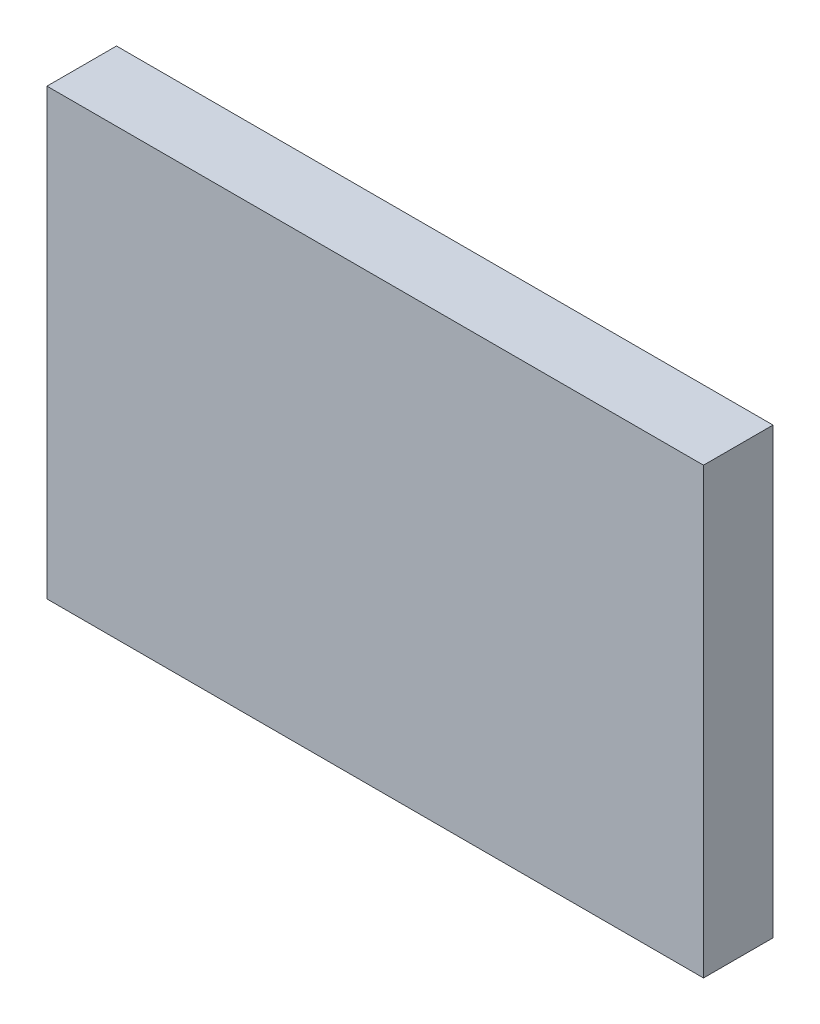
SolidWorks part; units mm, degrees
ref_plane "Alzado" through (0, 0, 0) normal (0, 0, 1) x (1, 0, 0)
ref_plane "Planta" through (0, 0, 0) normal (0, 1, 0) x (1, 0, 0)
ref_plane "Vista lateral" through (0, 0, 0) normal (1, 0, 0) x (0, 0, -1)
sketch "Croquis1" plane through (0, 0, 0) normal (0, 0, 1) x (1, 0, 0)
  line L1 (-85, -57.5) -> (85, -57.5)
  line L2 (-85, -57.5) -> (-85, 57.5)
  line L3 (-85, 57.5) -> (85, 57.5)
  line L4 (85, -57.5) -> (85, 57.5)
  line L5 (-85, -57.5) -> (85, 57.5) construction
  line L6 (-85, 57.5) -> (85, -57.5) construction
  point P0 (0, 0)
  dimension "D1" = 115
  dimension "D2" = 170
extrude "Saliente-Extruir1" add sketch "Croquis1" along normal blind 18
